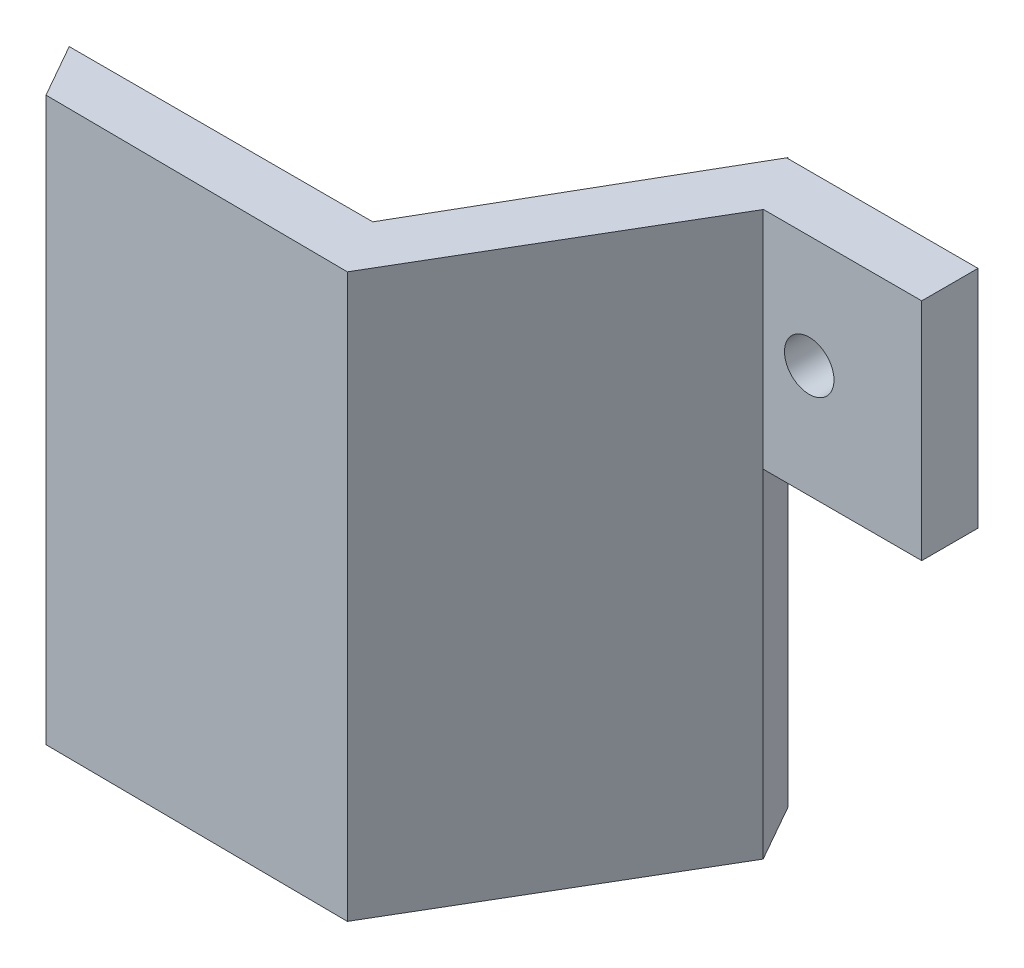
SolidWorks part; units mm, degrees
ref_plane "Plan de face" through (0, 0, 0) normal (0, 0, 1) x (1, 0, 0)
ref_plane "Plan de dessus" through (0, 0, 0) normal (0, 1, 0) x (1, 0, 0)
ref_plane "Plan de droite" through (0, 0, 0) normal (1, 0, 0) x (0, 0, -1)
sketch "Esquisse3" plane through (0, 0, 0) normal (0, 0, 1) x (1, 0, 0)
  line L1 (-9.1666, 8.4473) -> (10.8334, 8.4473)
  line L2 (-9.1666, 8.4473) -> (-9.1666, -11.5527)
  line L3 (-9.1666, -11.5527) -> (10.8334, -11.5527)
  line L4 (10.8334, 8.4473) -> (10.8334, -11.5527)
  dimension "D1" = 20
  dimension "D2" = 20
extrude "Boss.-Extru.2" add sketch "Esquisse3" along normal blind 5
sketch "Esquisse5" plane through (0, 0, 5) normal (0, 0, 1) x (1, 0, 0)
  line L0 (-9.1666, 8.4473) -> (-9.1666, -11.5527) construction
  line L2 (10.8334, 8.4473) -> (-9.1666, 8.4473) construction
  circle A0 centre (0.8334, -1.5527) radius 2.2
  dimension "D1" = 10
  dimension "D2" = 10
extrude "Enlèv. mat.-Extru.2" cut sketch "Esquisse5" against normal blind 5
sketch "Esquisse15" plane through (0, 8.4473, 0) normal (0, 1, 0) x (1, 0, 0)
  line L1 (-16.9237, -28.2934) -> (-3.2428, -5.0198)
  line L2 (-3.2428, -5.0198) -> (-16.5579, 18.4649)
  line L3 (-16.5579, 18.4649) -> (-43.5538, 18.6762)
  line L4 (-43.5538, 18.6762) -> (-57.2347, -4.5974)
  line L5 (-57.2347, -4.5974) -> (-43.9197, -28.0822)
  line L6 (-43.9197, -28.0822) -> (-16.9237, -28.2934)
  circle A0 centre (-30.2388, -4.8086) radius 23.3799 construction
extrude "Boss.-Extru.4" add sketch "Esquisse15" along normal blind 1 and the other way blind 50
sketch "Esquisse16" plane through (0, 9.4473, 0) normal (0, 1, 0) x (1, 0, 0)
  line L1 (-3.9717, 3.8287) -> (-19.643, 30.9723)
  line L2 (-19.643, 30.9723) -> (-50.9857, 30.9723)
  line L3 (-50.9857, 30.9723) -> (-66.6571, 3.8287)
  line L4 (-66.6571, 3.8287) -> (-50.9857, -23.3149)
  line L5 (-50.9857, -23.3149) -> (-19.643, -23.3149)
  line L6 (-19.643, -23.3149) -> (-3.9717, 3.8287)
  circle A0 centre (-35.3144, 3.8287) radius 27.1436 construction
extrude "Enlèv. mat.-Extru.3" cut sketch "Esquisse16" against normal blind 52
sketch "Esquisse17" plane through (0, 9.4473, 0) normal (0, 1, 0) x (1, 0, 0)
  line L1 (-47.5414, -30.6537) -> (-2.7687, -30.6537)
  line L2 (-47.5414, -30.6537) -> (-47.5414, 2.0183)
  line L3 (-47.5414, 2.0183) -> (-2.7687, 2.0183)
  line L4 (-2.7687, -30.6537) -> (-2.7687, 2.0183)
extrude "Enlèv. mat.-Extru.4" cut sketch "Esquisse17" against normal blind 1
